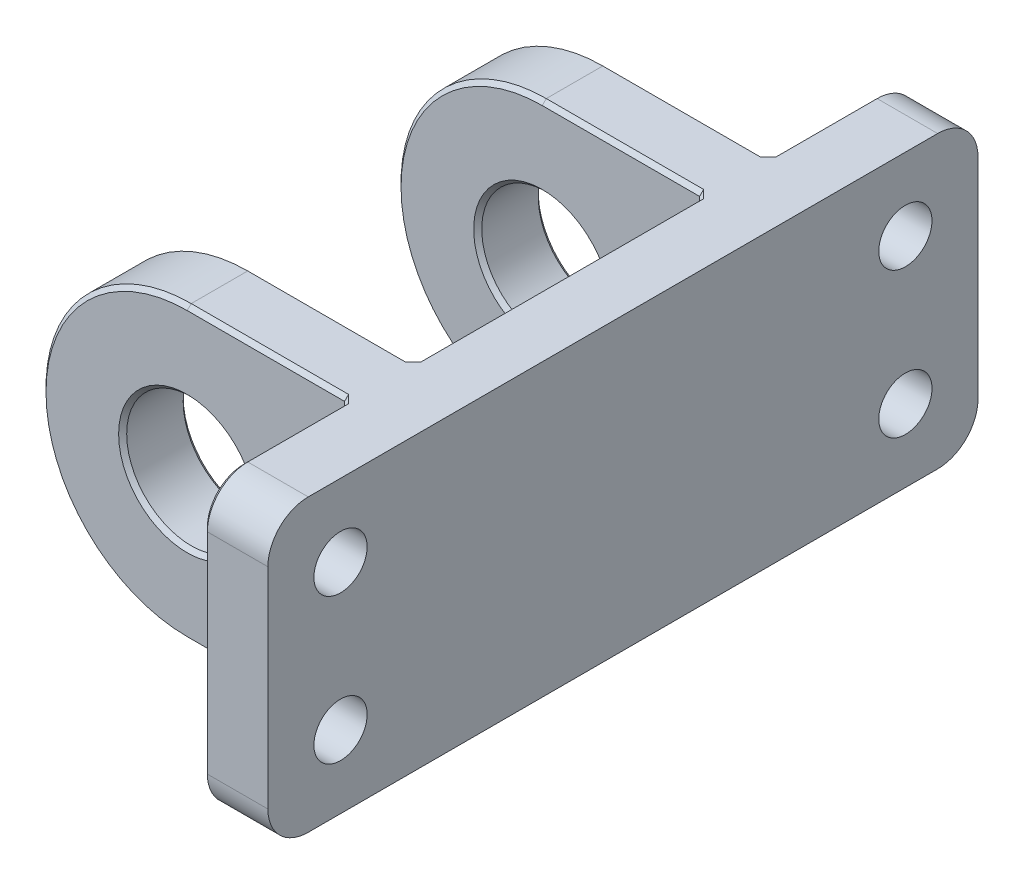
SolidWorks part; units mm, degrees
ref_plane "Front Plane" through (0, 0, 0) normal (0, 0, 1) x (1, 0, 0)
ref_plane "Top Plane" through (0, 0, 0) normal (0, 1, 0) x (1, 0, 0)
ref_plane "Right Plane" through (0, 0, 0) normal (1, 0, 0) x (0, 0, -1)
sketch "Sketch1" plane through (0, 0, 0) normal (0, 0, 1) x (1, 0, 0)
  line L0 (0, 0) -> (20, 0) construction
  line L1 (20, -18) -> (20, 18)
  line L3 (0, 18) -> (20, 18)
  line L5 (0, -18) -> (20, -18)
  circle A0 centre (0, 0) radius 8
  arc A1 (0, 18) -> (0, -18) centre (0, 0) ccw
  point P7 (20, 0)
  dimension "D1" = 90
  dimension "D2" = 36
  dimension "D3" = 20
extrude "Boss-Extrude1" add sketch "Sketch1" along normal blind 8
sketch "Sketch3" plane through (20, 0, 0) normal (1, 0, 0) x (0, 0, -1)
  line L0 (-26, 18) -> (18, 18)
  line L2 (-26, -18) -> (18, -18)
  line L3 (0, -18) -> (0, 18) construction
  line L4 (-26, -18) -> (-26, 18)
  line L5 (18, 18) -> (18, -18)
  line L8 (-8, -18) -> (-8, 18) construction
  line L9 (-8, 18) -> (0, 18) construction
  line L10 (-8, -18) -> (0, -18) construction
  dimension "D1" = 18
  dimension "D2" = 18
extrude "Boss-Extrude2" add sketch "Sketch3" along normal blind 8
sketch "Sketch5" plane through (20, 0, 0) normal (-1, 0, 0) x (0, 0, 1)
  line L0 (-18, 18) -> (0, 18) construction
  line L1 (-18, -18) -> (-18, 18) construction
  line L2 (0, -18) -> (-18, -18) construction
  point P0 (-9, 9)
  point P1 (-9, -9)
  dimension "D1" = 9
  dimension "D2" = 9
  dimension "D3" = 9
  dimension "D4" = 9
hole_wizard "CSK for M6 Countersunk Flat Head Screw1" positions "Sketch6" profile "Sketch7" countersink size "M6" standard "ISO"
sketch "Sketch6" plane through (20, 0, 0) normal (-1, 0, 0) x (0, 0, 1)
  point P0 (-9, 9)
  point P3 (-9, -9)
sketch "Sketch7" plane through (20, 9, -9) normal (0, 1, 0) x (0, 0, 1)
  line L0 (0, 0) -> (0, 13.9828)
  line L1 (0, 13.9828) -> (3.3, 12)
  line L2 (3.3, 12) -> (3.3, 3)
  line L3 (3.3, 3) -> (6.3, 0)
  line L5 (6.3, 0) -> (0, 0)
  line L6 (-3.3, 3) -> (-6.3, 0) construction
  line L10 (0, 13.9828) -> (-3.3, 12) construction
  line L11 (0, -6.35) -> (0, 107.95) construction
  dimension "Hole Dia." = 6.6
  dimension "Hole Depth" = 12
  dimension "Near C'Sink Dia." = 12.6
  dimension "Near C'Sink Angle" = 90
  dimension "Drill Angle" = 118
fillet "Fillet1" radius 5 2 edges at (24, -18, -18) (24, 18, -18)
mirror "Mirror1" about plane through (28, -18, 26) normal (0, 0, -1) of bodies 105
chamfer "Chamfer1" distance 0.5 angle 45 32 edges at (8, 0, 0) (8, 0, 8) (20, 0, 8) (10, 18, 8) (20, 18, 26) (20, -18, 26) (20, -18, -6.5) (20, 0, -18) (20, 18, -6.5) (20, 16.5355, -16.5355) (-18, 0, 8) (10, 18, 0) (20, -16.5355, -16.5355) (20, 0, 0) (10, -18, 0) (-18, 0, 0) (8, 0, 44) (-18, 0, 52) (10, -18, 52) (20, 0, 52) (10, 18, 52) (-18, 0, 44) (10, -18, 44) (10, 18, 44) (8, 0, 52) (20, 0, 70) (20, 18, 58.5) (20, -18, 58.5) (20, 0, 44) (20, -16.5355, 68.5355) (20, 16.5355, 68.5355) (10, -18, 8)
